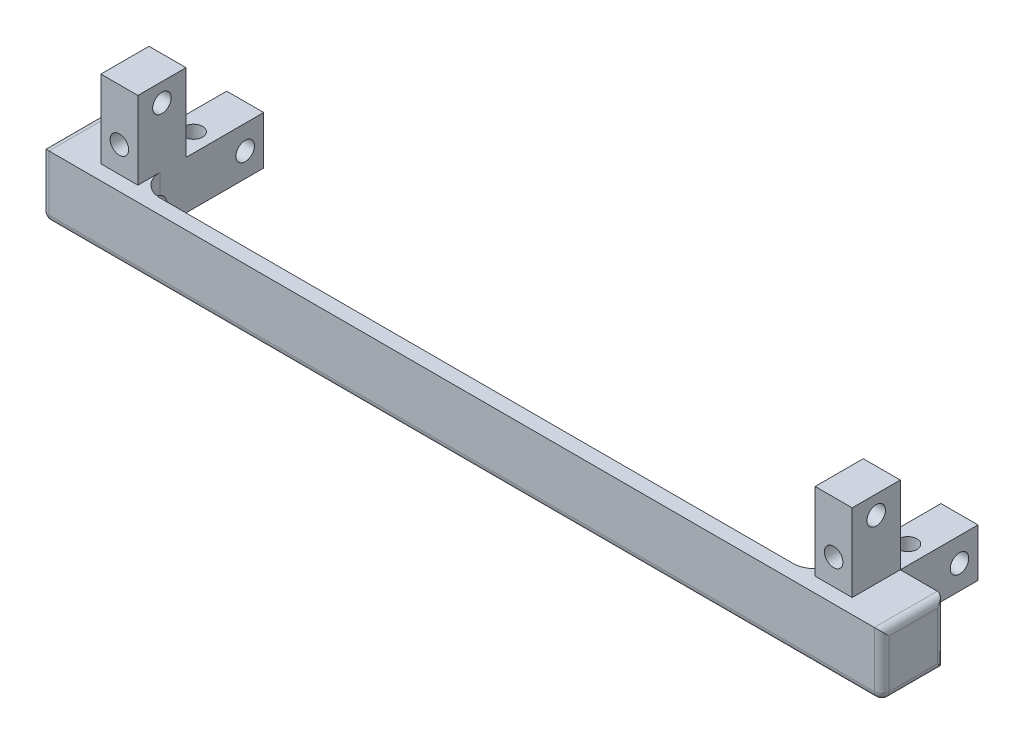
SolidWorks part; units mm, degrees
ref_plane "Front Plane" through (0, 0, 0) normal (0, 0, 1) x (1, 0, 0)
ref_plane "Top Plane" through (0, 0, 0) normal (0, 1, 0) x (1, 0, 0)
ref_plane "Right Plane" through (0, 0, 0) normal (1, 0, 0) x (0, 0, -1)
sketch "Sketch1" plane through (0, 0, 0) normal (0, 0, 1) x (1, 0, 0)
  line L1 (56.75, -4.25) -> (-56.75, -4.25)
  line L2 (56.75, -4.25) -> (56.75, 4.25)
  line L3 (56.75, 4.25) -> (-56.75, 4.25)
  line L4 (-56.75, -4.25) -> (-56.75, 4.25)
  line L5 (56.75, -4.25) -> (-56.75, 4.25) construction
  line L6 (56.75, 4.25) -> (-56.75, -4.25) construction
  point P0 (0, 0)
  dimension "D1" = 113.5
  dimension "D2" = 8.5
extrude "Boss-Extrude1" add sketch "Sketch1" along normal blind 8.5
ref_plane "Plane4" through (50.75, 0, 0) normal (1, 0, 0) x (0, 0, -1)
sketch "Sketch4" plane through (50.75, 0, 0) normal (1, 0, 0) x (0, 0, -1)
  line L0 (0, -2.25) -> (10.5, -2.25)
  line L1 (0, -4.25) -> (0, 4.25) construction
  line L2 (10.5, -2.25) -> (10.5, 14.75)
  line L3 (10.5, 14.75) -> (-6.5, 14.75)
  line L4 (-6.5, 14.75) -> (-6.5, 4.25)
  line L5 (-8.5, 4.25) -> (0, 4.25) construction
  line L6 (-8.5, -4.25) -> (0, -4.25) construction
  line L7 (-8.5, -4.25) -> (-8.5, 4.25) construction
  line L12 (0, -4.25) -> (0, 4.25)
  line L13 (0, 4.25) -> (-8.5, 4.25)
  line L14 (-8.5, 4.25) -> (-8.5, -4.25)
  line L15 (-8.5, -4.25) -> (0, -4.25)
  line L16 (0, -2.25) -> (0, 4.25)
  line L17 (0, 4.25) -> (-6.5, 4.25)
  dimension "D1" = 2
  dimension "D2" = 2
  dimension "D3" = 10.5
  dimension "D4" = 10.5
  dimension "D5" = 0
extrude "Boss-Extrude2" add sketch "Sketch4" against normal blind 5
ref_plane "Plane7" through (-50.75, 0, 0) normal (-1, 0, 0) x (0, 0, 1)
sketch "Sketch12" plane through (-50.75, 0, 0) normal (-1, 0, 0) x (0, 0, 1)
  line L0 (6.5, 4.25) -> (6.5, 14.75)
  line L1 (6.5, 14.75) -> (-10.5, 14.75)
  line L2 (-10.5, 14.75) -> (-10.5, -2.25)
  line L3 (-10.5, -2.25) -> (0, -2.25)
  line L4 (0, -2.25) -> (0, 4.25)
  line L5 (0, 4.25) -> (6.5, 4.25)
extrude "Boss-Extrude3" add sketch "Sketch12" against normal blind 5
sketch "Sketch13" plane through (0, 4.25, 0) normal (0, 1, 0) x (1, 0, 0)
  line L1 (-45.75, 0) -> (45.75, 0)
  line L2 (-45.75, 0) -> (-45.75, -6.5)
  line L3 (-45.75, -6.5) -> (45.75, -6.5)
  line L4 (45.75, 0) -> (45.75, -6.5)
extrude "Cut-Extrude1" cut sketch "Sketch13" against normal blind 6.5
hole_wizard "M3x0.5 Tapped Hole1" positions "Sketch16" profile "Sketch15" tap size "M3x0.5" standard "Ansi Metric"
sketch "Sketch16" plane through (0, 0, 6.5) normal (0, 0, 1) x (1, 0, 0)
  line L0 (-45.75, 4.25) -> (-50.75, 4.25) construction
  line L3 (-45.75, 4.25) -> (-45.75, 14.75) construction
  point P0 (-48.25, 7.75)
  dimension "D1" = 3.5
  dimension "D2" = 2.5
sketch "Sketch15" plane through (-48.25, 7.75, 6.5) normal (1, 0, 0) x (0, -1, 0)
  line L0 (0, 0) -> (0, 8.2511)
  line L1 (0, 8.2511) -> (1.25, 7.5)
  line L2 (1.25, 7.5) -> (1.25, 0)
  line L5 (1.25, 0) -> (0, 0)
  line L10 (0, 8.2511) -> (-1.25, 7.5) construction
  line L11 (0, -6.35) -> (0, 107.95) construction
  dimension "Tap Drill Dia." = 2.5
  dimension "Tap Drill Depth" = 7.5
  dimension "Drill Angle" = 118
cosmetic thread "Hole Thread1" parameters "D1"=6, "D2"=3
hole_wizard "M3x0.5 Tapped Hole2" positions "Sketch18" profile "Sketch19" tap size "M3x0.5" standard "Ansi Metric"
sketch "Sketch18" plane through (-50.75, 0, 0) normal (-1, 0, 0) x (0, 0, 1)
  line L0 (6.5, 4.25) -> (6.5, 14.75) construction
  line L1 (8.5, 4.25) -> (0, 4.25) construction
  point P0 (3.25, 12.25)
  dimension "D1" = 3.25
  dimension "D2" = 8
sketch "Sketch19" plane through (-50.75, 12.25, 3.25) normal (0, 1, 0) x (0, 0, 1)
  line L0 (0, 0) -> (0, 5)
  line L1 (0, 5) -> (1.25, 5)
  line L2 (1.25, 5) -> (1.25, 0)
  line L5 (1.25, 0) -> (0, 0)
  line L11 (0, -6.35) -> (0, 107.95) construction
  dimension "Thru Tap Drill Dia." = 2.5
  dimension "Thru Tap Drill Depth" = 5
cosmetic thread "Hole Thread9" parameters "D2"=3
hole_wizard "M3x0.5 Tapped Hole3" positions "Sketch21" profile "Sketch20" tap size "M3x0.5" standard "Ansi Metric"
sketch "Sketch21" plane through (-50.75, 0, 0) normal (-1, 0, 0) x (0, 0, 1)
  line L0 (0, 4.25) -> (0, -4.25) construction
  line L1 (-10.5, -2.25) -> (0, -2.25) construction
  point P0 (-8, 1)
  dimension "D1" = 8
  dimension "D2" = 3.25
cosmetic thread "Hole Thread3" parameters "D2"=3
sketch "Sketch20" plane through (-50.75, 1, -8) normal (0, 1, 0) x (0, 0, 1)
  line L0 (0, 0) -> (0, 5)
  line L1 (0, 5) -> (1.25, 5)
  line L2 (1.25, 5) -> (1.25, 0)
  line L5 (1.25, 0) -> (0, 0)
  line L11 (0, -6.35) -> (0, 107.95) construction
  dimension "Thru Tap Drill Dia." = 2.5
  dimension "Thru Tap Drill Depth" = 5
hole_wizard "M3x0.5 Tapped Hole4" positions "Sketch23" profile "Sketch22" tap size "M3x0.5" standard "Ansi Metric"
sketch "Sketch23" plane through (0, -2.25, 0) normal (0, -1, 0) x (1, 0, 0)
  line L1 (-45.75, -10.5) -> (-45.75, 0) construction
  line L2 (-56.75, 0) -> (56.75, 0) construction
  point P0 (-48.25, -3.5)
  dimension "D1" = 2.5
  dimension "D2" = 3.5
sketch "Sketch22" plane through (-48.25, -2.25, -3.5) normal (1, 0, 0) x (0, 0, -1)
  line L0 (0, 0) -> (0, 8.2511)
  line L1 (0, 8.2511) -> (1.25, 7.5)
  line L2 (1.25, 7.5) -> (1.25, 0)
  line L5 (1.25, 0) -> (0, 0)
  line L10 (0, 8.2511) -> (-1.25, 7.5) construction
  line L11 (0, -6.35) -> (0, 107.95) construction
  dimension "Tap Drill Dia." = 2.5
  dimension "Tap Drill Depth" = 7.5
  dimension "Drill Angle" = 118
cosmetic thread "Hole Thread5" parameters "D1"=6, "D2"=3
fillet "Fillet1" radius 1 1 edges at (0, -4.25, 8.5)
fillet "Fillet2" radius 1 5 edges at (-56.75, -4.25, 3.75) (-56.75, -3.9571, 8.2071) (-56.75, 4.25, 4.25) (-56.75, 0, 0) (-56.75, 0.5, 8.5)
fillet "Fillet3" radius 1 5 edges at (56.75, -4.25, 3.75) (56.75, -3.9571, 8.2071) (56.75, 0, 0) (56.75, 0.5, 8.5) (56.75, 4.25, 4.25)
fillet "Fillet4" radius 3 2 edges at (45.75, 1, 6.5) (-45.75, 1, 6.5)
hole_wizard "M3x0.5 Tapped Hole5" positions "Sketch28" profile "Sketch27" tap size "M3x0.5" standard "Ansi Metric"
sketch "Sketch28" plane through (0, 0, 6.5) normal (0, 0, 1) x (1, 0, 0)
  line L0 (45.75, 14.75) -> (45.75, 4.25) construction
  line L3 (45.75, 4.25) -> (50.75, 4.25) construction
  point P0 (48.25, 7.75)
  dimension "D1" = 2.5
  dimension "D2" = 3.5
sketch "Sketch27" plane through (48.25, 7.75, 6.5) normal (1, 0, 0) x (0, -1, 0)
  line L0 (0, 0) -> (0, 8.2511)
  line L1 (0, 8.2511) -> (1.25, 7.5)
  line L2 (1.25, 7.5) -> (1.25, 0)
  line L5 (1.25, 0) -> (0, 0)
  line L10 (0, 8.2511) -> (-1.25, 7.5) construction
  line L11 (0, -6.35) -> (0, 107.95) construction
  dimension "Tap Drill Dia." = 2.5
  dimension "Tap Drill Depth" = 7.5
  dimension "Drill Angle" = 118
cosmetic thread "Hole Thread6" parameters "D1"=6, "D2"=3
hole_wizard "M3x0.5 Tapped Hole6" positions "Sketch30" profile "Sketch29" tap size "M3x0.5" standard "Ansi Metric"
sketch "Sketch30" plane through (0, -2.25, 0) normal (0, -1, 0) x (1, 0, 0)
  line L0 (45.75, 0) -> (50.75, 0) construction
  line L1 (45.75, 0) -> (45.75, -10.5) construction
  point P0 (48.25, -3.5)
  dimension "D1" = 3.5
  dimension "D2" = 2.5
sketch "Sketch29" plane through (48.25, -2.25, -3.5) normal (1, 0, 0) x (0, 0, -1)
  line L0 (0, 0) -> (0, 8.2511)
  line L1 (0, 8.2511) -> (1.25, 7.5)
  line L2 (1.25, 7.5) -> (1.25, 0)
  line L5 (1.25, 0) -> (0, 0)
  line L10 (0, 8.2511) -> (-1.25, 7.5) construction
  line L11 (0, -6.35) -> (0, 107.95) construction
  dimension "Tap Drill Dia." = 2.5
  dimension "Tap Drill Depth" = 7.5
  dimension "Drill Angle" = 118
cosmetic thread "Hole Thread7" parameters "D1"=6, "D2"=3
hole_wizard "M3x0.5 Tapped Hole7" positions "Sketch32" profile "Sketch31" tap size "M3x0.5" standard "Ansi Metric"
sketch "Sketch32" plane through (50.75, 0, 0) normal (1, 0, 0) x (0, 0, -1)
  line L0 (0, 4.25) -> (0, -2.25) construction
  line L1 (0, -2.25) -> (10.5, -2.25) construction
  point P0 (8, 1)
  dimension "D1" = 8
  dimension "D2" = 3.25
sketch "Sketch31" plane through (50.75, 1, -8) normal (0, 1, 0) x (0, 0, -1)
  line L0 (0, 0) -> (0, 8.2511)
  line L1 (0, 8.2511) -> (1.25, 7.5)
  line L2 (1.25, 7.5) -> (1.25, 0)
  line L5 (1.25, 0) -> (0, 0)
  line L10 (0, 8.2511) -> (-1.25, 7.5) construction
  line L11 (0, -6.35) -> (0, 107.95) construction
  dimension "Tap Drill Dia." = 2.5
  dimension "Tap Drill Depth" = 7.5
  dimension "Drill Angle" = 118
cosmetic thread "Hole Thread8" parameters "D1"=5, "D2"=3
hole_wizard "M3x0.5 Tapped Hole9" positions "Sketch36" profile "Sketch35" tap size "M3x0.5" standard "Ansi Metric"
sketch "Sketch36" plane through (50.75, 0, 0) normal (1, 0, 0) x (0, 0, -1)
  line L0 (-6.5, 4.25) -> (0, 4.25) construction
  line L1 (-6.5, 14.75) -> (-6.5, 4.25) construction
  point P0 (-3.25, 12.25)
  dimension "D1" = 8
  dimension "D2" = 3.25
sketch "Sketch35" plane through (50.75, 12.25, 3.25) normal (0, 1, 0) x (0, 0, -1)
  line L0 (0, 0) -> (0, 8.2511)
  line L1 (0, 8.2511) -> (1.25, 7.5)
  line L2 (1.25, 7.5) -> (1.25, 0)
  line L5 (1.25, 0) -> (0, 0)
  line L10 (0, 8.2511) -> (-1.25, 7.5) construction
  line L11 (0, -6.35) -> (0, 107.95) construction
  dimension "Tap Drill Dia." = 2.5
  dimension "Tap Drill Depth" = 7.5
  dimension "Drill Angle" = 118
cosmetic thread "Hole Thread11" parameters "D1"=5, "D2"=3
sketch "Sketch43" plane through (-50.75, 0, 0) normal (-1, 0, 0) x (0, 0, 1)
  line L1 (6.5, 14.75) -> (-10.5, 14.75) construction
  line L2 (-10.5, 14.75) -> (-10.5, -2.25) construction
  line L3 (-10.5, 4.25) -> (-10.5, 14.75)
  line L4 (-10.5, 14.75) -> (0, 14.75)
  line L5 (-10.5, 4.25) -> (0, 4.25)
  line L6 (0, 4.25) -> (0, 14.75)
  point P6 (-5.25, 4.25)
  point P9 (-5.25, 9.5)
  point P10 (0, 9.5)
extrude "Cut-Extrude3" cut sketch "Sketch43" against normal through all
hole_wizard "#8-36 Tapped Hole1" positions "Sketch45" profile "Sketch44" tap size "#8-36" standard "Ansi Inch"
sketch "Sketch45" plane through (-56.75, 0, 0) normal (-1, 0, 0) x (0, 0, 1)
  line L0 (7.5, -4.25) -> (0, -4.25) construction
  line L1 (8.5, 4.25) -> (8.5, -3.25) construction
  point P0 (4.25, 0)
  dimension "D1" = 4.25
  dimension "D2" = 4.25
sketch "Sketch44" plane through (-56.75, 0, 4.25) normal (0, 1, 0) x (0, 0, 1)
  line L0 (0, 0) -> (0, 13.1378)
  line L1 (0, 13.1378) -> (1.7272, 12.1)
  line L2 (1.7272, 12.1) -> (1.7272, 0)
  line L5 (1.7272, 0) -> (0, 0)
  line L10 (0, 13.1378) -> (-1.7272, 12.1) construction
  line L11 (0, -6.35) -> (0, 107.95) construction
  dimension "Tap Drill Dia." = 3.4544
  dimension "Tap Drill Depth" = 12.1
  dimension "Drill Angle" = 118
cosmetic thread "Hole Thread12" parameters "D1"=12, "D2"=4.1656
